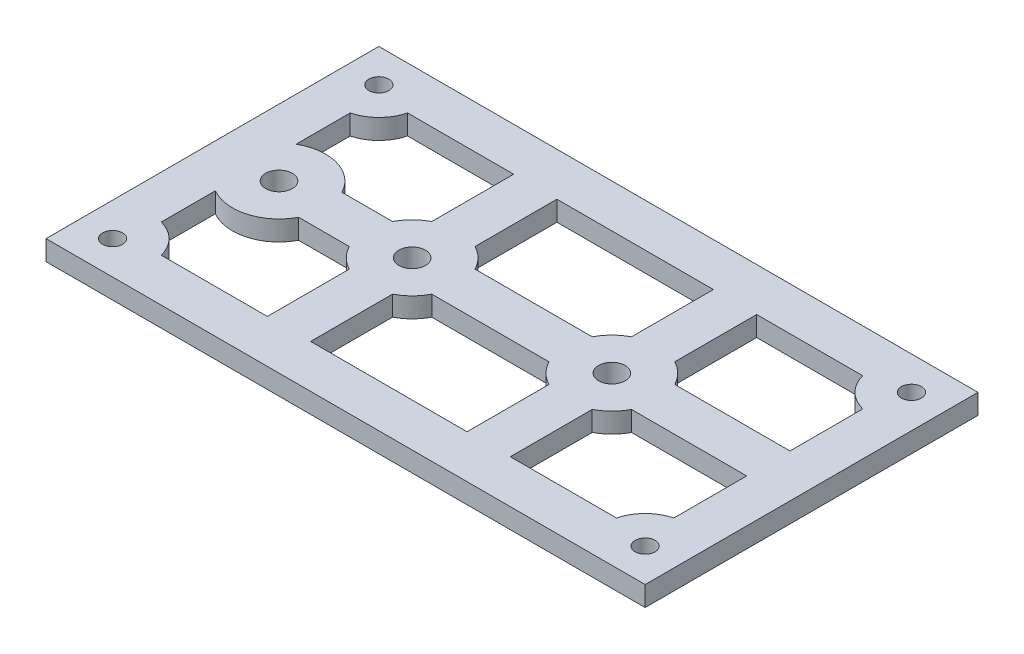
SolidWorks part; units mm, degrees
ref_plane "Front Plane" through (0, 0, 0) normal (0, 0, 1) x (1, 0, 0)
ref_plane "Top Plane" through (0, 0, 0) normal (0, 1, 0) x (1, 0, 0)
ref_plane "Right Plane" through (0, 0, 0) normal (1, 0, 0) x (0, 0, -1)
sketch "Sketch1" plane through (0, 0, 0) normal (0, 1, 0) x (1, 0, 0)
  line L1 (-45, 25) -> (45, 25)
  line L2 (-45, 25) -> (-45, -25)
  line L3 (-45, -25) -> (45, -25)
  line L4 (45, 25) -> (45, -25)
  point P0 (0, 0)
  point P6 (0, 0)
  dimension "D1" = 90
  dimension "D2" = 50
extrude "Boss-Extrude1" add sketch "Sketch1" along normal blind 3
sketch "Sketch2" plane through (0, 3, 0) normal (0, 1, 0) x (1, 0, 0)
  line L0 (-45, 25) -> (-45, -25) construction
  line L5 (38.5, -14.1905) -> (38.5, -6.0622)
  line L11 (34.1905, -18.5) -> (18.25, -18.5)
  line L12 (0, 0) -> (-49.4034, 0) construction
  line L13 (0, 0) -> (0, -29.3954) construction
  line L33 (-34.1905, -18.5) -> (-18.25, -18.5)
  line L34 (-38.5, -14.1905) -> (-38.5, -6.0622)
  line L35 (-28.8002, -3.25) -> (-21.1998, -3.25)
  line L36 (-18.25, -18.5) -> (-18.25, -6.1998)
  line L37 (-45, -25) -> (45, -25) construction
  line L38 (-15, 0) -> (-15, -27.6325) construction
  line L39 (18.25, -18.5) -> (18.25, -6.1998)
  line L40 (28.8002, -3.25) -> (21.1998, -3.25)
  line L41 (38.5, 14.1905) -> (38.5, 6.0622)
  line L42 (34.1905, 18.5) -> (18.25, 18.5)
  line L43 (18.25, 18.5) -> (18.25, 6.1998)
  line L44 (28.8002, 3.25) -> (21.1998, 3.25)
  line L45 (-38.5, 14.1905) -> (-38.5, 6.0622)
  line L46 (-34.1905, 18.5) -> (-18.25, 18.5)
  line L47 (-18.25, 18.5) -> (-18.25, 6.1998)
  line L48 (-28.8002, 3.25) -> (-21.1998, 3.25)
  line L49 (28.8002, 3.25) -> (38.5, 3.25)
  line L50 (38.5, 3.25) -> (38.5, 6.0622)
  line L51 (28.8002, -3.25) -> (38.5, -3.25)
  line L52 (38.5, -3.25) -> (38.5, -6.0622)
  line L53 (-11.75, 18.5) -> (11.75, 18.5)
  line L54 (-11.75, -18.5) -> (11.75, -18.5)
  line L55 (-11.75, -18.5) -> (-11.75, -6.1998)
  line L56 (-8.8002, -3.25) -> (8.8002, -3.25)
  line L57 (11.75, -18.5) -> (11.75, -6.1998)
  line L58 (11.75, 18.5) -> (11.75, 6.1998)
  line L59 (-8.8002, 3.25) -> (8.8002, 3.25)
  line L60 (-11.75, 18.5) -> (-11.75, 6.1998)
  arc A4 (-38.5, -6.0622) -> (-28.8002, -3.25) centre (-35, 0) ccw
  circle A5 centre (-40, -20) radius 1.5
  arc A6 (-38.5, -14.1905) -> (-34.1905, -18.5) centre (-40, -20) cw
  arc A7 (-21.1998, -3.25) -> (-18.25, -6.1998) centre (-15, 0) ccw
  circle A8 centre (40, -20) radius 1.5
  arc A10 (38.5, -14.1905) -> (34.1905, -18.5) centre (40, -20) ccw
  arc A11 (21.1998, -3.25) -> (18.25, -6.1998) centre (15, 0) cw
  circle A12 centre (40, 20) radius 1.5
  arc A13 (38.5, 14.1905) -> (34.1905, 18.5) centre (40, 20) cw
  arc A14 (21.1998, 3.25) -> (18.25, 6.1998) centre (15, 0) ccw
  arc A16 (-38.5, 6.0622) -> (-28.8002, 3.25) centre (-35, 0) cw
  arc A17 (-38.5, 14.1905) -> (-34.1905, 18.5) centre (-40, 20) ccw
  arc A18 (-21.1998, 3.25) -> (-18.25, 6.1998) centre (-15, 0) cw
  circle A19 centre (-40, 20) radius 1.5
  arc A20 (-11.75, -6.1998) -> (-8.8002, -3.25) centre (-15, 0) ccw
  arc A21 (8.8002, -3.25) -> (11.75, -6.1998) centre (15, 0) ccw
  arc A22 (8.8002, 3.25) -> (11.75, 6.1998) centre (15, 0) cw
  arc A23 (-11.75, 6.1998) -> (-8.8002, 3.25) centre (-15, 0) cw
  point P0 (0, 0)
  dimension "D7" = 5
  dimension "D5" = 7
  dimension "D6" = 3
  dimension "D9" = 6
  dimension "D10" = 7
  dimension "D14" = 7
  dimension "D15" = 7
  dimension "D1" = 6.5
  dimension "D2" = 6.5
  dimension "D3" = 3.25
  dimension "D4" = 3.25
  dimension "D8" = 5
  dimension "D11" = 3.25
  dimension "D12" = 6.5
  dimension "D13" = 3.25
sketch "Sketch3" plane through (0, 3, 0) normal (0, 1, 0) x (1, 0, 0)
  line L0 (0, 0) -> (-45.0632, 0) construction
  line L1 (-45, 25) -> (-45, -25) construction
  line L2 (0, 0) -> (42.7297, 0) construction
  circle A0 centre (-35, 0) radius 2
  circle A1 centre (-15, 0) radius 2
  circle A2 centre (15, 0) radius 2
  dimension "D1" = 4
  dimension "D3" = 4
  dimension "D5" = 4
  dimension "D2" = 10
  dimension "D4" = 20
  dimension "D6" = 30
extrude "Cut-Extrude2" cut sketch "Sketch3" against normal blind 10
extrude "Cut-Extrude3" cut sketch "Sketch2" against normal blind 10
